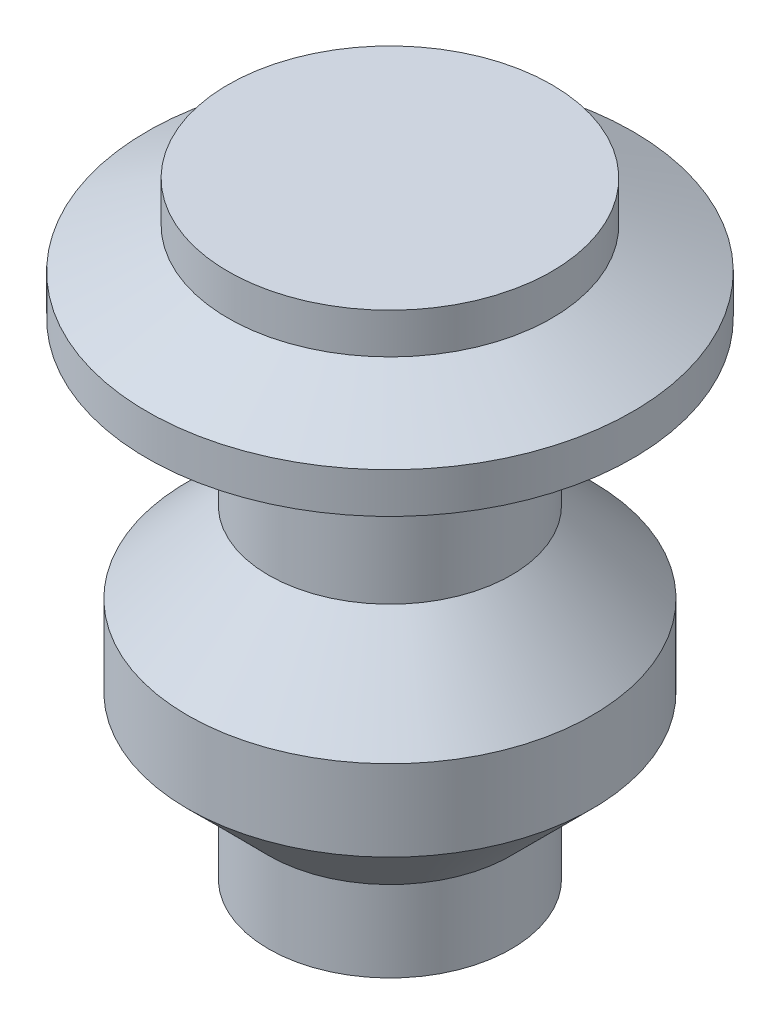
SolidWorks part; units mm, degrees
ref_plane "前视基准面" through (0, 0, 0) normal (0, 0, 1) x (1, 0, 0)
ref_plane "上视基准面" through (0, 0, 0) normal (0, 1, 0) x (1, 0, 0)
ref_plane "右视基准面" through (0, 0, 0) normal (1, 0, 0) x (0, 0, -1)
other "Configuration Table"
sketch "草图1" plane through (0, 0, 0) normal (0, 0, 1) x (1, 0, 0)
  line L0 (0, 0) -> (0, 150) construction
  line L1 (30, 0) -> (30, 20)
  line L2 (30, 20) -> (50, 40)
  line L3 (50, 40) -> (50, 60)
  line L4 (50, 60) -> (30, 80)
  line L5 (30, 80) -> (30, 100)
  line L6 (30, 100) -> (60, 120)
  line L7 (60, 120) -> (60, 130)
  line L8 (60, 130) -> (40, 140)
  line L9 (40, 140) -> (40, 150)
  line L10 (40, 150) -> (0, 150)
  line L11 (0, 150) -> (0, 0)
  line L12 (0, 0) -> (30, 0)
revolve "旋转1" add sketch "草图1" angle 360 about L0
